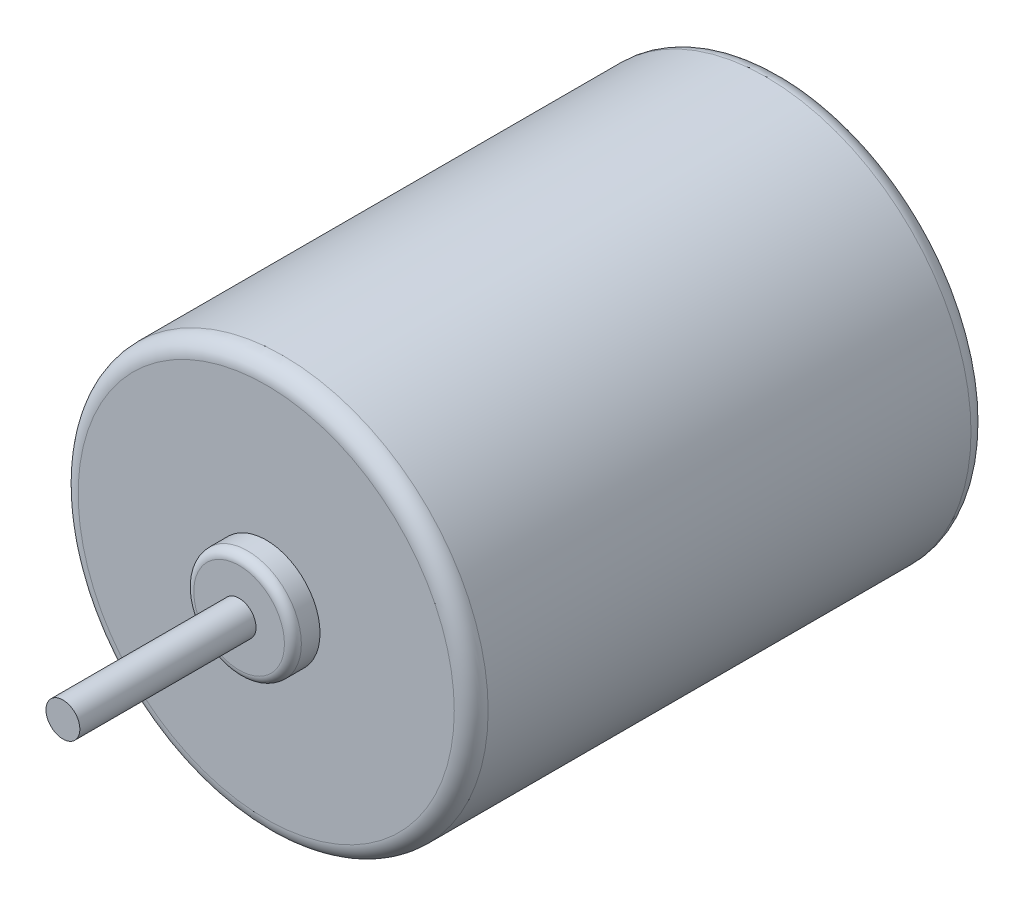
SolidWorks part; units mm, degrees
ref_plane "Front Plane" through (0, 0, 0) normal (0, 0, 1) x (1, 0, 0)
ref_plane "Top Plane" through (0, 0, 0) normal (0, 1, 0) x (1, 0, 0)
ref_plane "Right Plane" through (0, 0, 0) normal (1, 0, 0) x (0, 0, -1)
sketch "Sketch1" plane through (0, 0, 0) normal (0, 0, 1) x (1, 0, 0)
  circle A0 centre (0, 0) radius 12.1
  dimension "D1" = 24.2
extrude "Boss-Extrude1" add sketch "Sketch1" along normal blind 30.5
sketch "Sketch2" plane through (0, 0, 30.5) normal (0, 0, 1) x (1, 0, 0)
  circle A0 centre (0, 0) radius 3.175
  dimension "D1" = 6.35
extrude "Boss-Extrude2" add sketch "Sketch2" along normal blind 1.6
sketch "Sketch3" plane through (0, 0, 32.1) normal (0, 0, 1) x (1, 0, 0)
  circle A0 centre (0, 0) radius 1
  dimension "D1" = 2
extrude "Boss-Extrude3" add sketch "Sketch3" along normal blind 10.4
sketch "Sketch4" plane through (0, 0, 0) normal (0, 0, -1) x (-1, 0, 0)
  circle A0 centre (0, 0) radius 4.25
  dimension "D1" = 8.5
extrude "Boss-Extrude4" add sketch "Sketch4" along normal blind 2
fillet "Fillet1" radius 1 2 edges at (12.1, 0, 30.5) (12.1, 0, 0)
fillet "Fillet2" radius 0.5 2 edges at (3.175, 0, 32.1) (-4.25, 0, -2)
